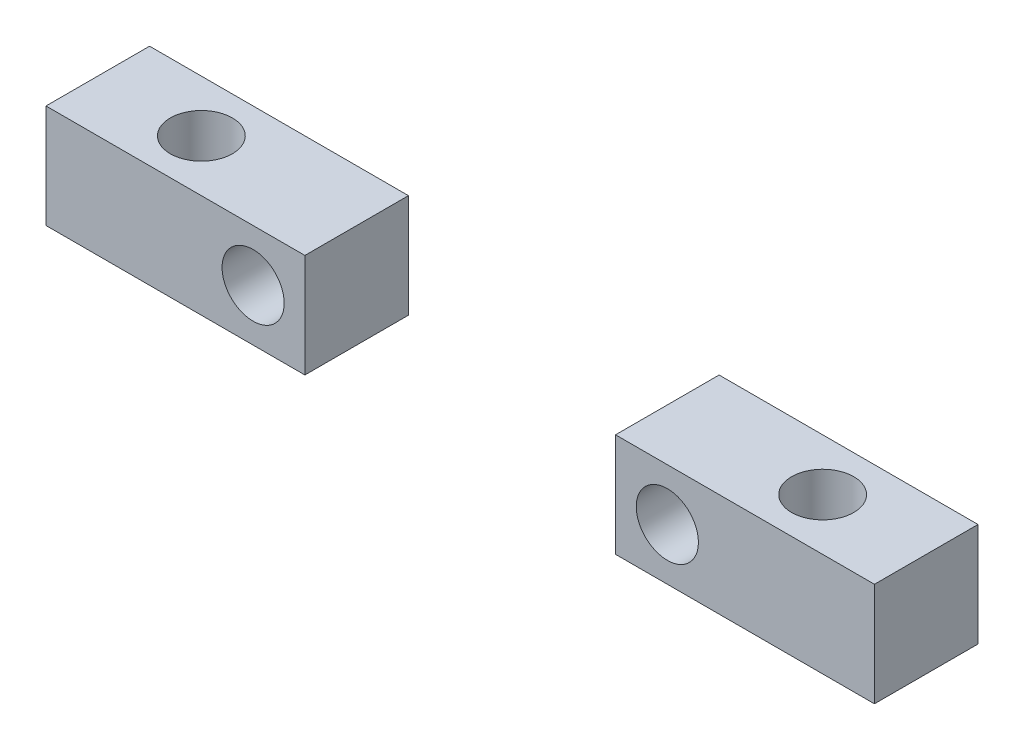
SolidWorks part; units mm, degrees
ref_plane "Plan de face" through (0, 0, 0) normal (0, 0, 1) x (1, 0, 0)
ref_plane "Plan de dessus" through (0, 0, 0) normal (0, 1, 0) x (1, 0, 0)
ref_plane "Plan de droite" through (0, 0, 0) normal (1, 0, 0) x (0, 0, -1)
sketch "Esquisse1" plane through (0, 0, 0) normal (0, 1, 0) x (1, 0, 0)
  line L1 (-40, 10) -> (40, 10)
  line L2 (-40, 10) -> (-40, 0)
  line L3 (-40, 0) -> (40, 0)
  line L4 (40, 10) -> (40, 0)
  dimension "D1" = 40
  dimension "D2" = 80
  dimension "D3" = 10
extrude "Extrusion1" add sketch "Esquisse1" along normal blind 10
sketch "Esquisse2" plane through (0, 0, 0) normal (0, 0, 1) x (1, 0, 0)
  line L0 (40, 10) -> (40, 0) construction
  line L1 (-40, 10) -> (40, 10) construction
  circle A0 centre (20, 5) radius 3
  circle A1 centre (-20, 5) radius 3
  dimension "D1" = 6
  dimension "D2" = 20
  dimension "D3" = 5
extrude "Extrusion2" cut sketch "Esquisse2" against normal through all
sketch "Esquisse3" plane through (0, 10, 0) normal (0, 1, 0) x (1, 0, 0)
  line L0 (40, 0) -> (40, 10) construction
  line L1 (40, 10) -> (-40, 10) construction
  circle A0 centre (30, 5) radius 3
  circle A1 centre (-30, 5) radius 3
  dimension "D1" = 6
  dimension "D2" = 10
  dimension "D3" = 5
extrude "Extrusion3" cut sketch "Esquisse3" against normal through all
sketch "Esquisse4" plane through (0, 0, 0) normal (0, 0, 1) x (1, 0, 0)
  line L1 (-15, 16.4217) -> (15, 16.4217)
  line L2 (-15, 16.4217) -> (-15, -9.5846)
  line L3 (-15, -9.5846) -> (15, -9.5846)
  line L4 (15, 16.4217) -> (15, -9.5846)
  dimension "D1" = 30
  dimension "D2" = 15
extrude "Extrusion4" cut sketch "Esquisse4" against normal through all
